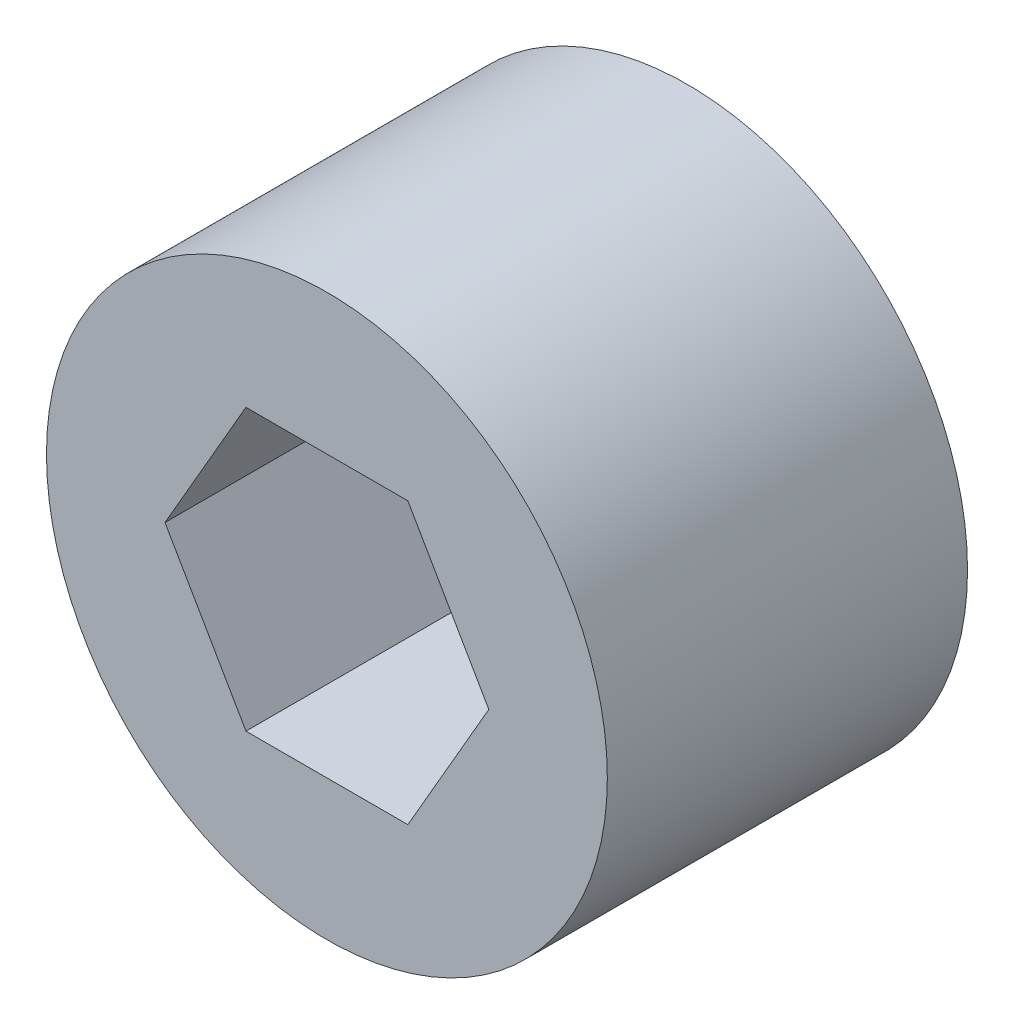
SolidWorks part; units mm, degrees
material "6061 Alloy"
ref_plane "Front Plane" through (0, 0, 0) normal (0, 0, 1) x (1, 0, 0)
ref_plane "Top Plane" through (0, 0, 0) normal (0, 1, 0) x (1, 0, 0)
ref_plane "Right Plane" through (0, 0, 0) normal (1, 0, 0) x (0, 0, -1)
sketch "Sketch1" plane through (0, 0, 0) normal (0, 0, 1) x (1, 0, 0)
  line L1 (-7.3323, 0) -> (-3.6662, -6.35)
  line L2 (-3.6662, -6.35) -> (3.6662, -6.35)
  line L3 (3.6662, -6.35) -> (7.3323, 0)
  line L4 (7.3323, 0) -> (3.6662, 6.35)
  line L5 (3.6662, 6.35) -> (-3.6662, 6.35)
  line L6 (-3.6662, 6.35) -> (-7.3323, 0)
  circle A0 centre (0, 0) radius 12.7
  circle A1 centre (0, 0) radius 6.35 construction
  dimension "D2" = 25.4
  dimension "D1" = 12.7
extrude "Boss-Extrude1" add sketch "Sketch1" along normal mid plane 16.3119
